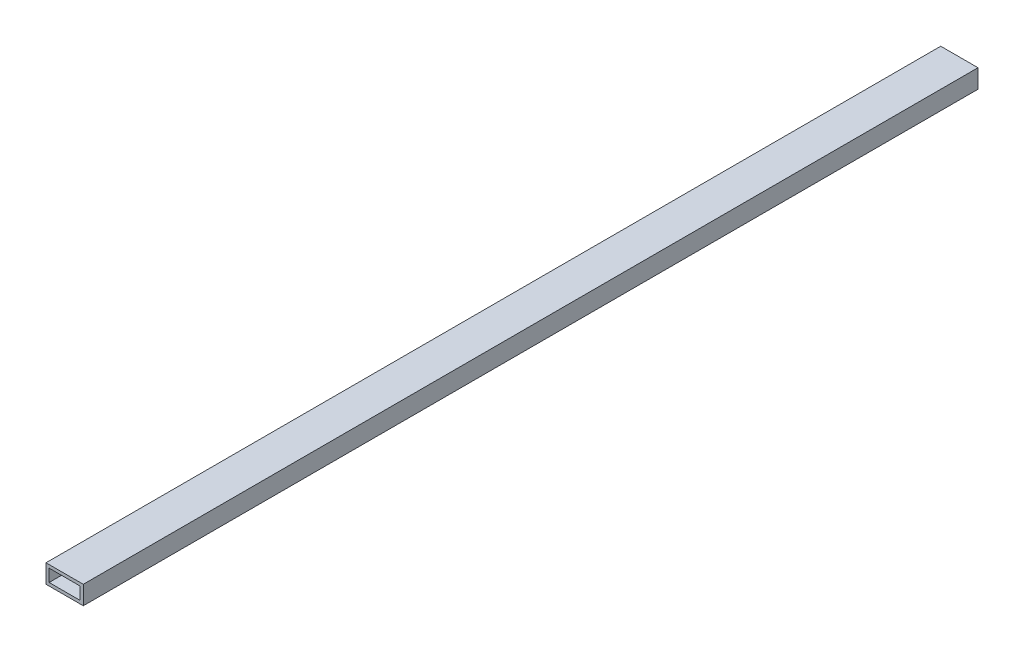
SolidWorks part; units mm, degrees
ref_plane "Front Plane" through (0, 0, 0) normal (0, 0, 1) x (1, 0, 0)
ref_plane "Top Plane" through (0, 0, 0) normal (0, 1, 0) x (1, 0, 0)
ref_plane "Right Plane" through (0, 0, 0) normal (1, 0, 0) x (0, 0, -1)
sketch "Sketch1" plane through (0, 0, 0) normal (0, 0, 1) x (1, 0, 0)
  line L0 (-15.875, 6.35) -> (15.875, 6.35)
  line L2 (-19.05, 9.525) -> (19.05, 9.525)
  line L3 (-19.05, 9.525) -> (-19.05, -9.525)
  line L4 (-19.05, -9.525) -> (19.05, -9.525)
  line L5 (19.05, 9.525) -> (19.05, -9.525)
  line L10 (15.875, 6.35) -> (15.875, -6.35)
  line L11 (-15.875, -6.35) -> (15.875, -6.35)
  line L12 (-15.875, 6.35) -> (-15.875, -6.35)
  point P12 (0, 9.525)
  point P14 (19.05, 0)
  dimension "Wall Thickness" = 3.175
  dimension "Outside Width" = 38.1
  dimension "Outside Height" = 19.05
  dimension "Inside Height" = 12.7
  dimension "Inside Width" = 31.75
sketch "Sketch2" plane through (0, 0, 0) normal (1, 0, 0) x (0, 0, -1)
  line L0 (457.2, 0) -> (-457.2, 0)
  point P4 (0, 0)
  point P7 (-457.2, 0)
  point P10 (457.2, 0)
  dimension "Length" = 914.4
sketch "Sketch3" plane through (0, 0, 0) normal (0, 0, 1) x (1, 0, 0)
  line L21 (19.05, 9.525) -> (-19.05, 9.525)
  line L22 (19.05, -9.525) -> (19.05, 9.525)
  line L23 (-19.05, -9.525) -> (19.05, -9.525)
  line L24 (-19.05, 9.525) -> (-19.05, -9.525)
  line L25 (19.05, 9.525) -> (-19.05, 9.525)
  line L26 (19.05, -9.525) -> (19.05, 9.525)
  line L27 (-19.05, -9.525) -> (19.05, -9.525)
  line L28 (-19.05, 9.525) -> (-19.05, -9.525)
  line L29 (15.875, 6.35) -> (-15.875, 6.35)
  line L30 (15.875, -6.35) -> (15.875, 6.35)
  line L31 (-15.875, -6.35) -> (15.875, -6.35)
  line L32 (-15.875, 6.35) -> (-15.875, -6.35)
  line L33 (15.875, 6.35) -> (-15.875, 6.35)
  line L34 (15.875, -6.35) -> (15.875, 6.35)
  line L35 (-15.875, -6.35) -> (15.875, -6.35)
  line L36 (-15.875, 6.35) -> (-15.875, -6.35)
  dimension "D1" = 0
  dimension "D2" = 0
extrude "Boss-Extrude1" add sketch "Sketch3" along normal up to vertex (457.2 mm away) and the other way up to vertex (457.2 mm away) up to point (0, 0, 457.2) other way up to point (0, 0, -457.2)
sketch "Drawing Reference" plane through (0, 0, 0) normal (1, 0, 0) x (0, 0, -1)
  line L0 (-457.2, 0) -> (457.2, 0) construction
  line L1 (0, -9.525) -> (0, 9.525) construction
  line L2 (-457.2, -9.525) -> (457.2, -9.525) construction
  line L5 (-457.2, 9.525) -> (457.2, 9.525) construction
  point P7 (-429.768, 0)
  point P8 (429.768, 0)
  dimension "D1" = 27.432
equation "\"D1@Drawing Reference\"=\"Outside Width@Sketch1\" * 0.72"
